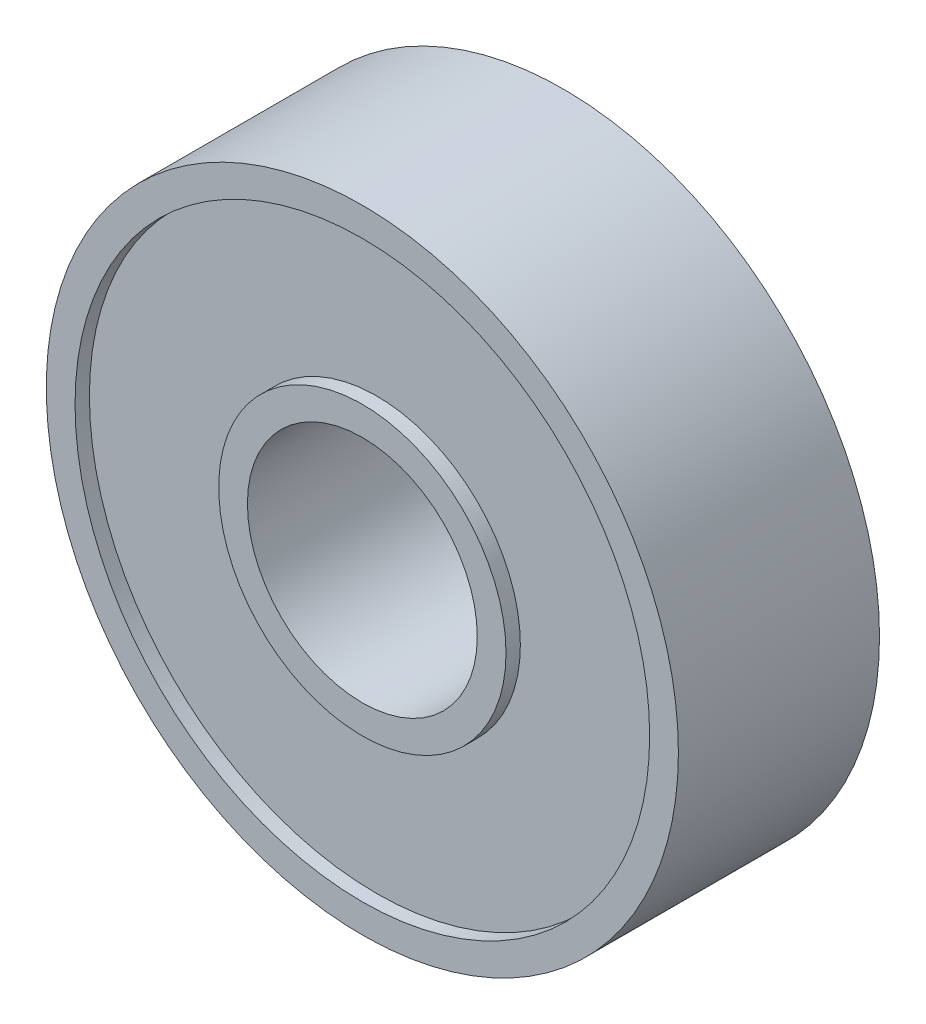
SolidWorks part; units mm, degrees
ref_plane "Alzado" through (0, 0, 0) normal (0, 0, 1) x (1, 0, 0)
ref_plane "Planta" through (0, 0, 0) normal (0, 1, 0) x (1, 0, 0)
ref_plane "Vista lateral" through (0, 0, 0) normal (1, 0, 0) x (0, 0, -1)
sketch "Croquis1" plane through (0, 0, 0) normal (0, 0, 1) x (1, 0, 0)
  circle A0 centre (0, 0) radius 11
  dimension "D1" = 22
extrude "Saliente-Extruir1" add sketch "Croquis1" along normal blind 7
sketch "Croquis2" plane through (0, 0, 7) normal (0, 0, 1) x (1, 0, 0)
  circle A0 centre (0, 0) radius 4
  dimension "D1" = 8
extrude "Cortar-Extruir1" cut sketch "Croquis2" against normal blind 7
sketch "Croquis3" plane through (0, 0, 7) normal (0, 0, 1) x (1, 0, 0)
  circle A0 centre (0, 0) radius 5
  circle A1 centre (0, 0) radius 10
  circle A2 centre (0, 0) radius 4 construction
  circle A3 centre (0, 0) radius 11 construction
  dimension "D1" = 1
  dimension "D2" = 1
extrude "Cortar-Extruir2" cut sketch "Croquis3" against normal blind 0.5
sketch "Croquis4" plane through (0, 0, 0) normal (0, 0, -1) x (-1, 0, 0)
  circle A0 centre (0, 0) radius 5
  circle A1 centre (0, 0) radius 10
  circle A2 centre (0, 0) radius 4 construction
  circle A3 centre (0, 0) radius 11 construction
  dimension "D1" = 1
  dimension "D2" = 1
extrude "Cortar-Extruir3" cut sketch "Croquis4" against normal blind 0.5
